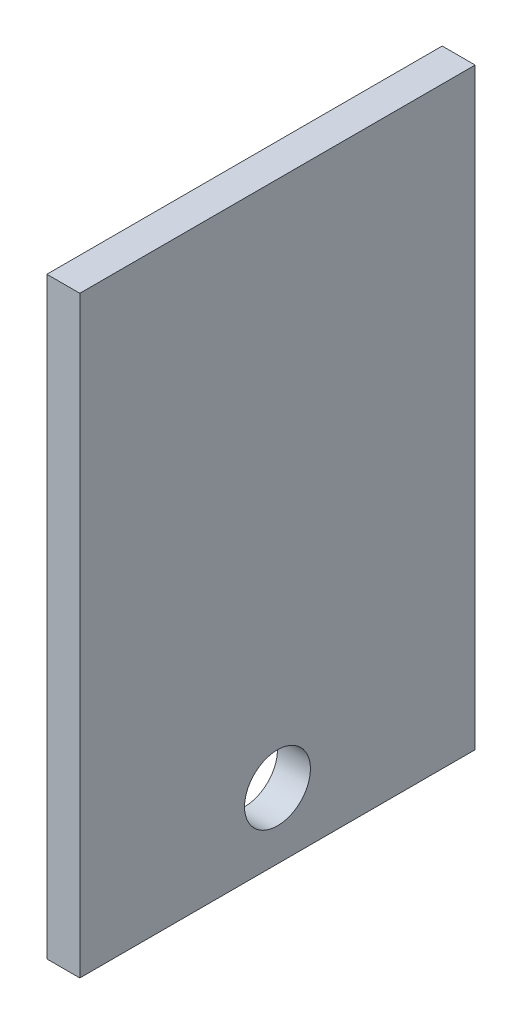
SolidWorks part; units mm, degrees
material "Pine"
ref_plane "Alzado" through (0, 0, 0) normal (0, 0, 1) x (1, 0, 0)
ref_plane "Planta" through (0, 0, 0) normal (0, 1, 0) x (1, 0, 0)
ref_plane "Vista lateral" through (0, 0, 0) normal (1, 0, 0) x (0, 0, -1)
sketch "Sketch1" plane through (0, 0, 0) normal (1, 0, 0) x (0, 0, -1)
  line L1 (-152.4, -152.4) -> (152.4, -152.4)
  line L2 (-152.4, -152.4) -> (-152.4, 152.4)
  line L3 (-152.4, 152.4) -> (152.4, 152.4)
  line L4 (152.4, -152.4) -> (152.4, 152.4)
  line L5 (-152.4, -152.4) -> (152.4, 152.4) construction
  line L6 (-152.4, 152.4) -> (152.4, -152.4) construction
  point P0 (0, 0)
  dimension "D1" = 304.8
  dimension "D2" = 304.8
extrude "Boss-Extrude1" add sketch "Sketch1" along normal blind 25.4
sketch "Sketch2" plane through (0, 0, 0) normal (-1, 0, 0) x (0, 0, 1)
  line L0 (152.4, -152.4) -> (-152.4, -152.4) construction
  circle A0 centre (0, -101.6) radius 25.4
  point P4 (54.7689, -101.6)
  dimension "D1" = 50.8
  dimension "D2" = 25.4
extrude "Cut-Extrude1" cut sketch "Sketch2" against normal up to surface (25.4 mm away) contours A0 up to face at (25.4, 0, 0)
sketch "Sketch3" plane through (0, 152.4, 0) normal (0, 1, 0) x (1, 0, 0)
  line L1 (0, 152.4) -> (25.4, 152.4)
  line L2 (0, 152.4) -> (0, -152.4)
  line L3 (0, -152.4) -> (25.4, -152.4)
  line L4 (25.4, 152.4) -> (25.4, -152.4)
extrude "Boss-Extrude2" add sketch "Sketch3" along normal blind 152.4
